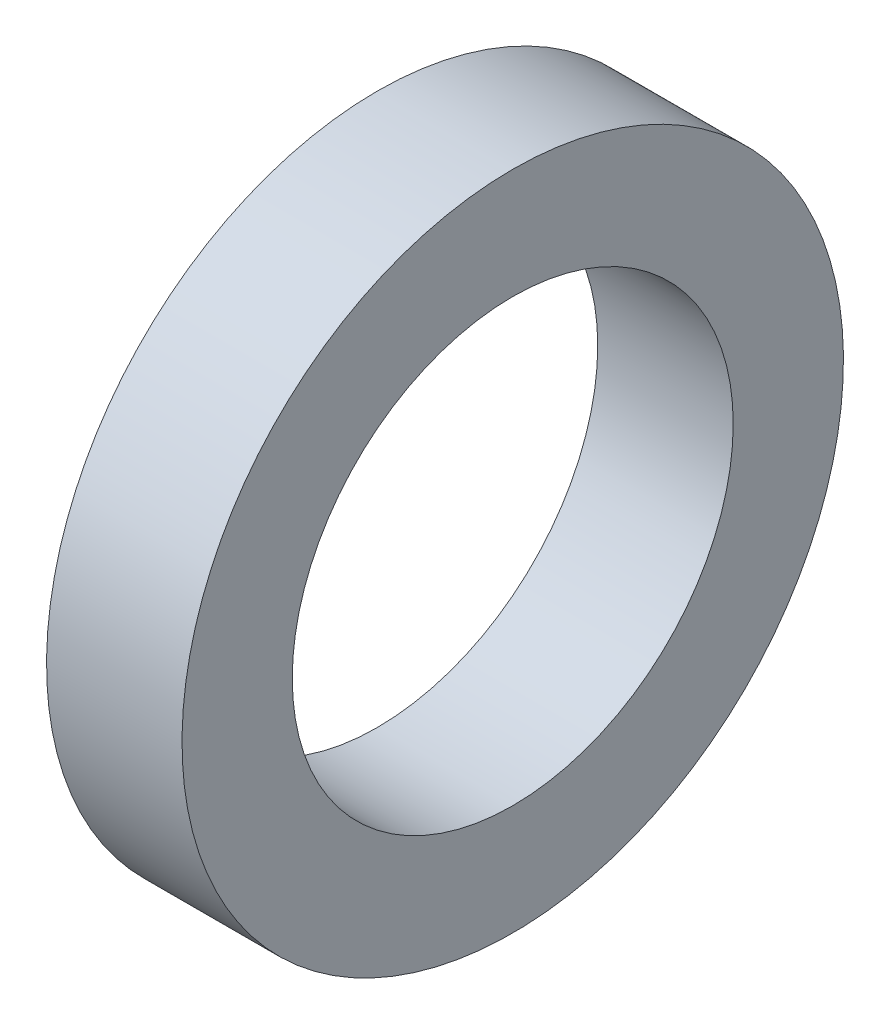
SolidWorks part; units mm, degrees
ref_plane "Front Plane" through (0, 0, 0) normal (0, 0, 1) x (1, 0, 0)
ref_plane "Top Plane" through (0, 0, 0) normal (0, 1, 0) x (1, 0, 0)
ref_plane "Right Plane" through (0, 0, 0) normal (1, 0, 0) x (0, 0, -1)
sketch "Sketch1" plane through (0, 0, 0) normal (0, 0, 1) x (1, 0, 0)
  line L0 (0, 0) -> (0, 9.525)
  line L1 (0, 9.525) -> (3.9014, 9.525)
  line L2 (3.9014, 9.525) -> (3.9014, 6.35)
  line L3 (3.9014, 6.35) -> (3.9014, 0)
  line L4 (3.9014, 0) -> (0, 0)
  line L5 (3.9014, 6.35) -> (0, 6.35)
  dimension "D1" = 3.9014
  dimension "D2" = 9.525
  dimension "D3" = 6.35
revolve "Revolve1" add sketch "Sketch1" angle 360 about L4
